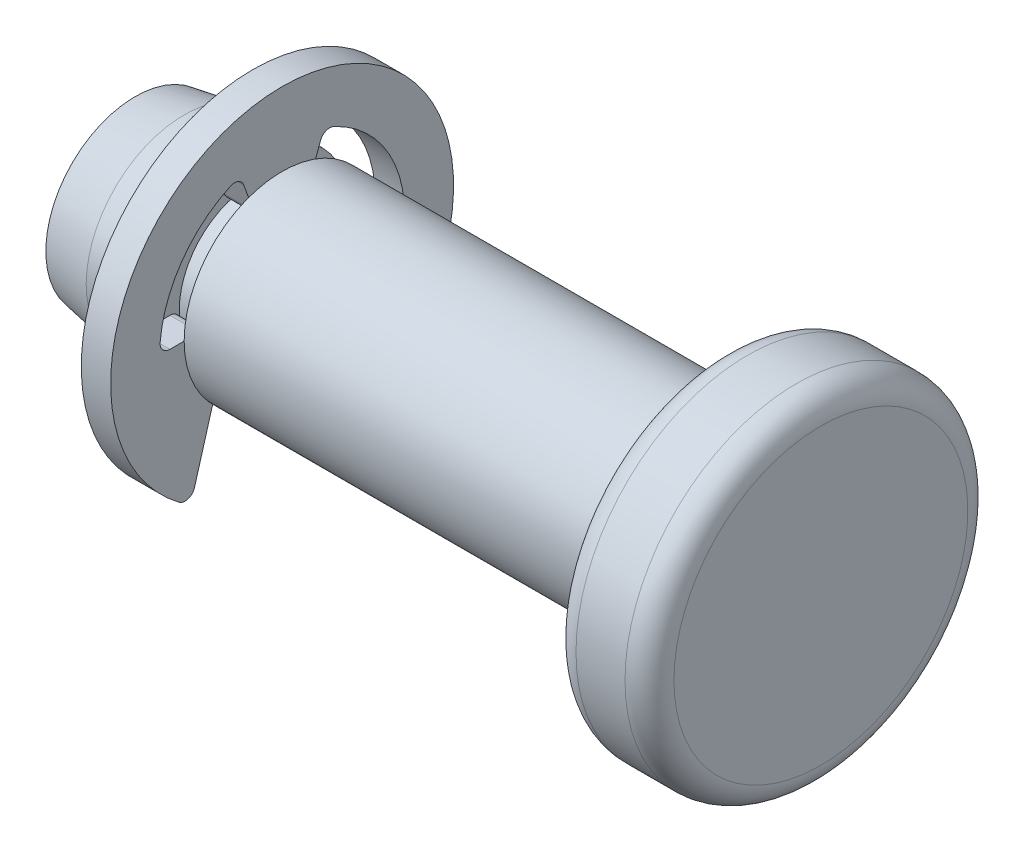
SolidWorks part; units mm, degrees
material "AISI 304"
ref_plane "前视基准面" through (0, 0, 0) normal (0, 0, 1) x (1, 0, 0)
ref_plane "上视基准面" through (0, 0, 0) normal (0, 1, 0) x (1, 0, 0)
ref_plane "右视基准面" through (0, 0, 0) normal (1, 0, 0) x (0, 0, -1)
sketch "草图1" plane through (0, 0, 0) normal (0, 1, 0) x (1, 0, 0)
  line L0 (-14, 0) -> (0, 0)
  line L1 (0, 0) -> (0, 3.5)
  line L2 (0, 3.5) -> (-2, 3.5)
  line L3 (-2, 3.5) -> (-2, 2)
  line L4 (-2, 2) -> (-11, 2)
  line L5 (-11, 2) -> (-11, 1.5)
  line L6 (-11, 1.5) -> (-11.6, 1.5)
  line L7 (-11.6, 1.5) -> (-11.6, 2)
  line L8 (-11.6, 2) -> (-14, 2)
  line L9 (-14, 2) -> (-14, 0)
  dimension "R_head" = 3.5
  dimension "T" = 2
  dimension "R_body" = 2
  dimension "R_socket" = 1.5
  dimension "t_socket" = 0.6
  dimension "L" = 12
  dimension "L_use" = 9
revolve "旋转1" add sketch "草图1" angle 360 about L0
chamfer "倒角1" distance 1 angle 10 1 edges at (-14, 0, 2)
fillet "圆角1" radius 0.5 2 edges at (0, 0, 3.5) (-2, 0, 3.5)
sketch "草图3" plane through (-11, 0, 0) normal (-1, 0, 0) x (0, 0, 1)
  line L0 (-1.25, -0.8292) -> (1.25, -0.8292) construction
  line L1 (-1.5, 0) -> (-2.5, 0)
  line L2 (0, 3.5) -> (0, 1.5) construction
  line L3 (-0.513, 1.4095) -> (-0.8551, 2.3492)
  line L4 (-1.25, -0.8292) -> (-1.8656, -2.9613)
  line L5 (1.25, -0.8292) -> (1.8656, -2.9613)
  line L6 (1.5, 0) -> (2.5, 0)
  line L7 (0.513, 1.4095) -> (0.8551, 2.3492)
  arc A0 (1.8656, -2.9613) -> (-1.8656, -2.9613) centre (0, 0) ccw
  arc A1 (1.25, -0.8292) -> (1.5, 0) centre (0, 0) ccw
  arc A2 (-2.5, 0) -> (-0.8551, 2.3492) centre (0, 0) cw
  arc A3 (2.5, 0) -> (0.8551, 2.3492) centre (0, 0) ccw
  arc A4 (-1.5, 0) -> (-1.25, -0.8292) centre (0, 0) ccw
  arc A5 (0.513, 1.4095) -> (-0.513, 1.4095) centre (0, 0) ccw
  point P17 (0, 2.5)
  dimension "E_ring_D" = 7
  dimension "E_ring_di" = 3
  dimension "E_ring_H" = 2.5
  dimension "D4" = 20
extrude "凸台-拉伸2" add sketch "草图3" along normal blind 0.6 separate body
fillet "圆角2" radius 0.2 12 edges at (-11.3, -2.9613, 1.8656) (-11.3, -0.8292, -1.25) (-11.3, -2.9613, -1.8656) (-11.3, -0.8292, 1.25) (-11.3, 0, 1.5) (-11.3, 0, 2.5) (-11.3, 2.3492, 0.8551) (-11.3, 1.4095, 0.513) (-11.3, 1.4095, -0.513) (-11.3, 2.3492, -0.8551) (-11.3, 0, -2.5) (-11.3, 0, -1.5)
other "冻结***"
